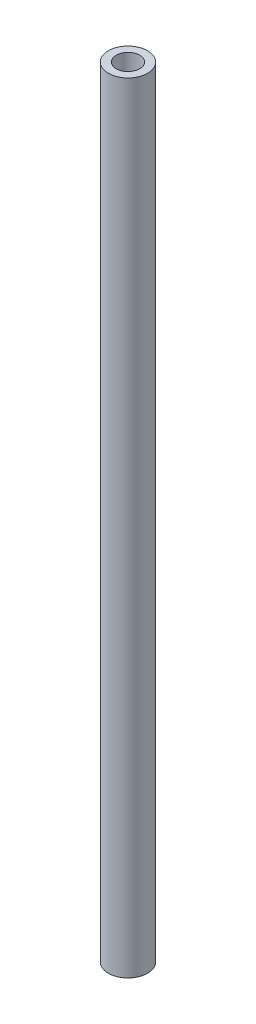
SolidWorks part; units mm, degrees
ref_plane "Front Plane" through (0, 0, 0) normal (0, 0, 1) x (1, 0, 0)
ref_plane "Top Plane" through (0, 0, 0) normal (0, 1, 0) x (1, 0, 0)
ref_plane "Right Plane" through (0, 0, 0) normal (1, 0, 0) x (0, 0, -1)
sketch "Sketch2" plane through (0, 0, 0) normal (0, 1, 0) x (1, 0, 0)
  circle A0 centre (0, 0) radius 1.5
  circle A1 centre (0, 0) radius 2.5
  dimension "D1" = 3
  dimension "D2" = 5
extrude "Boss-Extrude1" add sketch "Sketch2" along normal blind 99.5
